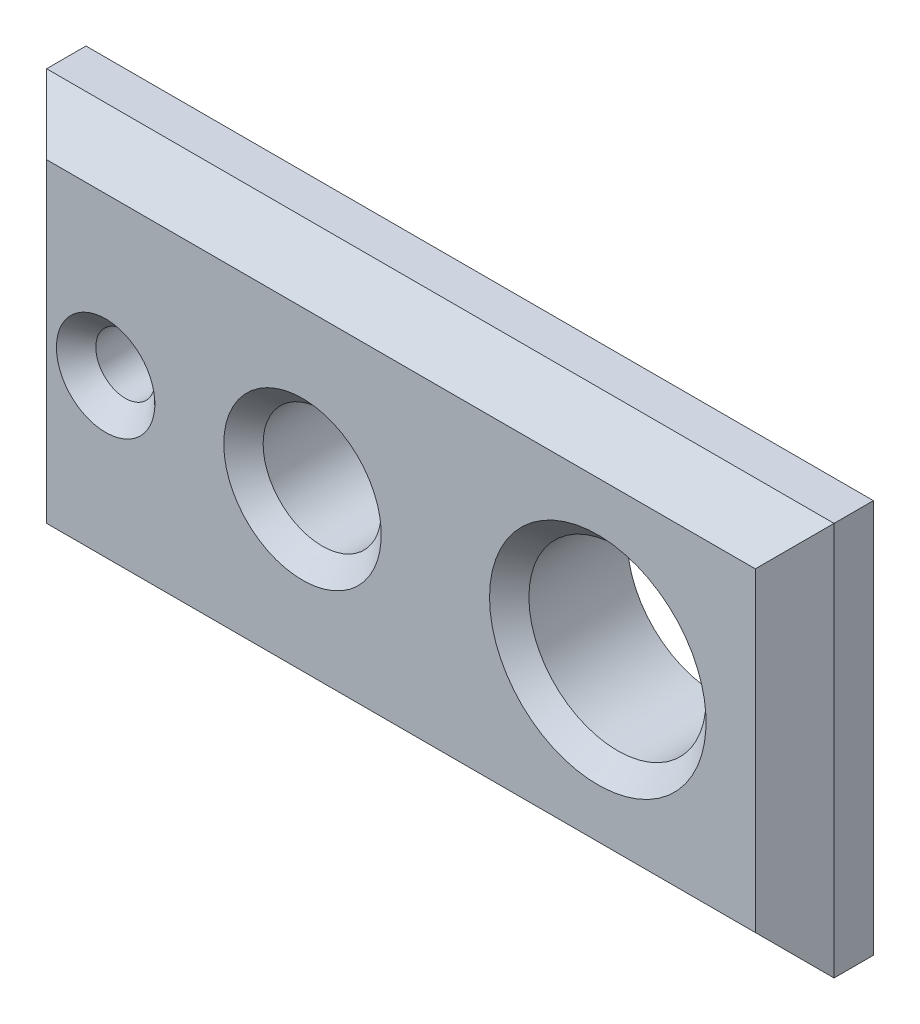
SolidWorks part; units mm, degrees
ref_plane "Front Plane" through (0, 0, 0) normal (0, 0, 1) x (1, 0, 0)
ref_plane "Top Plane" through (0, 0, 0) normal (0, 1, 0) x (1, 0, 0)
ref_plane "Right Plane" through (0, 0, 0) normal (1, 0, 0) x (0, 0, -1)
sketch "Sketch1" plane through (0, 0, 0) normal (0, 0, 1) x (1, 0, 0)
  line L1 (100, 50) -> (-100, 50)
  line L2 (100, 50) -> (100, -50)
  line L3 (100, -50) -> (-100, -50)
  line L4 (-100, 50) -> (-100, -50)
  line L5 (100, 50) -> (-100, -50) construction
  line L6 (100, -50) -> (-100, 50) construction
  point P0 (0, 0)
  dimension "D1" = 100
  dimension "D2" = 200
extrude "Boss-Extrude1" add sketch "Sketch1" along normal mid plane 30
chamfer "Chamfer1" distance 10 angle 45 8 edges at (0, -50, -15) (100, 0, -15) (0, 50, -15) (-100, 0, -15) (0, 50, 15) (100, 0, 15) (0, -50, 15) (-100, 0, 15)
sketch "Sketch2" plane through (0, 0, 15) normal (0, 0, 1) x (1, 0, 0)
  line L0 (-90, 0) -> (90, 0) construction
  line L1 (-90, 40) -> (-90, -40) construction
  line L2 (90, -40) -> (90, 40) construction
  line L3 (-100, -50) -> (-100, 50) construction
  circle A0 centre (-75, 0) radius 7.5
  circle A1 centre (-25, 0) radius 15
  circle A2 centre (50, 0) radius 22.5
  dimension "D4" = 15
  dimension "D5" = 30
  dimension "D6" = 45
  dimension "D1" = 25
  dimension "D2" = 50
  dimension "D3" = 75
extrude "Cut-Extrude1" cut sketch "Sketch2" against normal blind 30
chamfer "Chamfer2" distance 5 angle 45 3 edges at (72.5, 0, 15) (-10, 0, 15) (-67.5, 0, 15)
